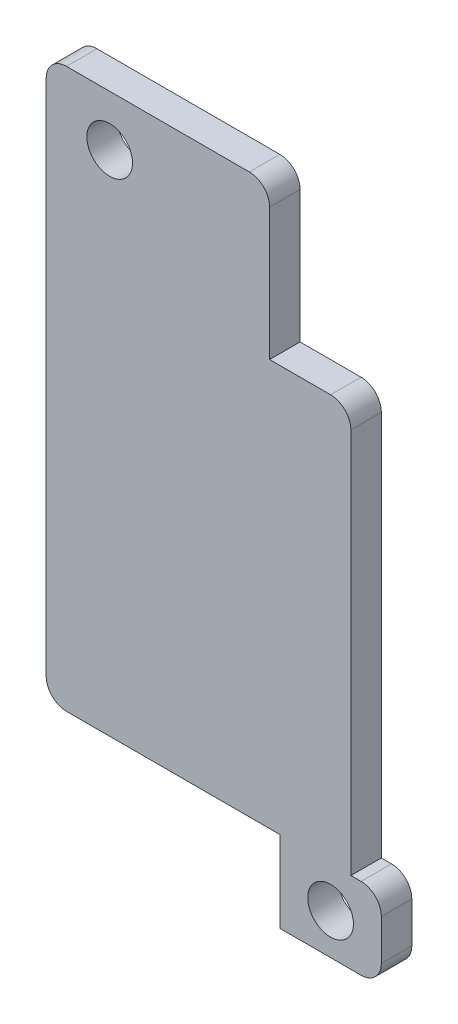
SolidWorks part; units mm, degrees
ref_plane "Front Plane" through (0, 0, 0) normal (0, 0, 1) x (1, 0, 0)
ref_plane "Top Plane" through (0, 0, 0) normal (0, 1, 0) x (1, 0, 0)
ref_plane "Right Plane" through (0, 0, 0) normal (1, 0, 0) x (0, 0, -1)
sketch "Sketch1" plane through (0, 0, 0) normal (0, 0, 1) x (1, 0, 0)
  line L1 (-14.0559, 16.0015) -> (15.9441, 16.0015)
  line L2 (-14.0559, 16.0015) -> (-14.0559, -38.9985)
  line L3 (-14.0559, -38.9985) -> (15.9441, -38.9985)
  line L4 (15.9441, 16.0015) -> (15.9441, -38.9985)
  dimension "D1" = 30
  dimension "D2" = 55
extrude "Boss-Extrude1" add sketch "Sketch1" along normal mid plane 3
sketch "Sketch2" plane through (0, 0, 1.5) normal (0, 0, 1) x (1, 0, 0)
  line L0 (15.9441, 16.0015) -> (-14.0559, 16.0015) construction
  line L1 (7.9441, 16.0015) -> (15.9441, 16.0015)
  line L2 (7.9441, 16.0015) -> (7.9441, 1.0015)
  line L3 (7.9441, 1.0015) -> (15.9441, 1.0015)
  line L4 (15.9441, 16.0015) -> (15.9441, 1.0015)
  line L5 (15.9441, -38.9985) -> (15.9441, 16.0015) construction
  dimension "D1" = 8
  dimension "D2" = 15
extrude "Cut-Extrude1" cut sketch "Sketch2" against normal through all
sketch "Sketch3" plane through (0, -38.9985, 0) normal (0, -1, 0) x (-1, 0, 0)
  line L0 (14.0559, -1.5) -> (-15.9441, -1.5) construction
  line L1 (-15.9441, 1.5) -> (-8.9441, 1.5)
  line L2 (-15.9441, 1.5) -> (-15.9441, -1.5)
  line L3 (-15.9441, -1.5) -> (-8.9441, -1.5)
  line L4 (-8.9441, 1.5) -> (-8.9441, -1.5)
  dimension "D1" = 7
extrude "Boss-Extrude2" add sketch "Sketch3" along normal blind 8
sketch "Sketch6" plane through (15.9441, 0, 0) normal (1, 0, 0) x (0, 0, -1)
  line L0 (1.5, -46.9985) -> (1.5, 1.0015) construction
  line L1 (-1.5, -46.9985) -> (1.5, -46.9985)
  line L2 (-1.5, -46.9985) -> (-1.5, -38.9985)
  line L3 (-1.5, -38.9985) -> (1.5, -38.9985)
  line L4 (1.5, -46.9985) -> (1.5, -38.9985)
  dimension "D1" = 8
extrude "Boss-Extrude3" add sketch "Sketch6" along normal blind 3
hole_wizard "M4 Clearance Hole1" positions "Sketch4" profile "Sketch5" hole size "M4" standard "ANSI Metric" end condition through all
sketch "Sketch4" plane through (0, 0, 1.5) normal (0, 0, 1) x (1, 0, 0)
  point P0 (-7.8059, 11.0015)
  point P2 (13.9441, -42.9985)
  point P8 (13.9441, -42.9985)
sketch "Sketch5" plane through (-7.8059, 11.0015, 1.5) normal (1, 0, 0) x (0, -1, 0)
  line L0 (0, 0) -> (0, 3)
  line L1 (0, 3) -> (2.25, 3)
  line L2 (2.25, 3) -> (2.25, 0)
  line L5 (2.25, 0) -> (0, 0)
  line L11 (0, -6.35) -> (0, 107.95) construction
  dimension "Thru Hole Dia." = 4.5
  dimension "Thru Hole Depth" = 3
fillet "Fillet1" radius 2 6 edges at (-14.0559, -38.9985, 0) (-14.0559, 16.0015, 0) (15.9441, 1.0015, 0) (7.9441, 16.0015, 0) (18.9441, -46.9985, 0) (18.9441, -38.9985, 0)
